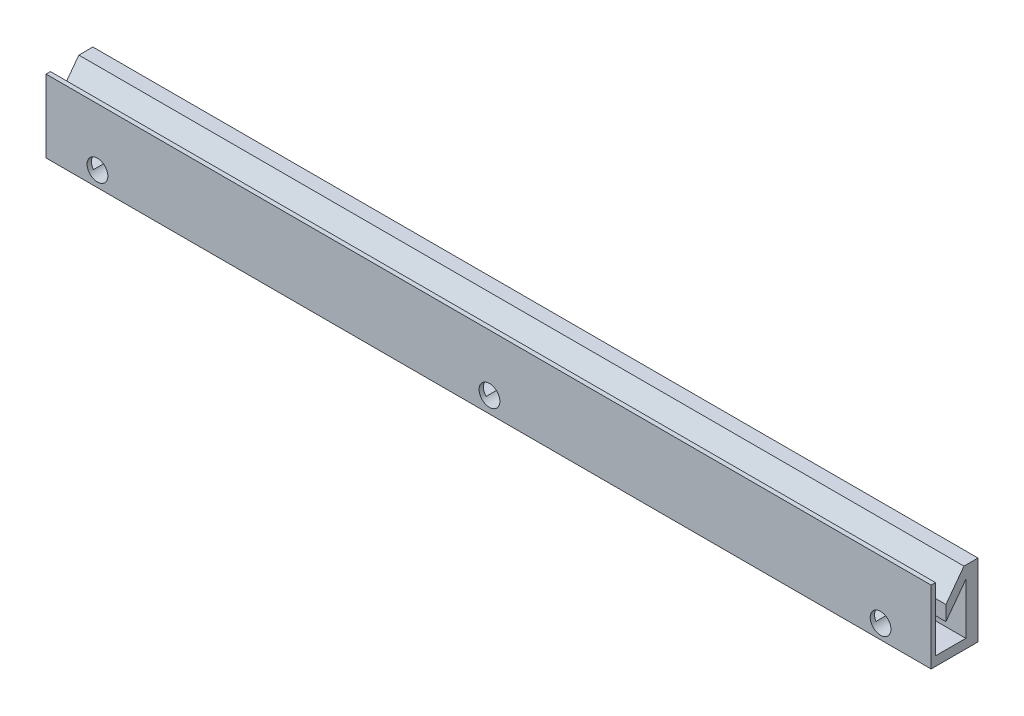
SolidWorks part; units mm, degrees
ref_plane "Front Plane" through (0, 0, 0) normal (0, 0, 1) x (1, 0, 0)
ref_plane "Top Plane" through (0, 0, 0) normal (0, 1, 0) x (1, 0, 0)
ref_plane "Right Plane" through (0, 0, 0) normal (1, 0, 0) x (0, 0, -1)
sketch "Sketch1" plane through (0, 0, 0) normal (1, 0, 0) x (0, 0, -1)
  line L0 (0.083, 0.3694) -> (0.083, 17.0567)
  line L1 (0.083, 17.0567) -> (1.083, 17.0567)
  line L2 (1.083, 17.0567) -> (1.083, 2.4843)
  line L3 (1.083, 2.4843) -> (8.0526, 2.4843)
  line L4 (8.0526, 2.4843) -> (8.0526, 14.2178)
  line L5 (8.0526, 14.2178) -> (3.483, 8.0815)
  line L6 (3.483, 8.0815) -> (3.483, 11.4955)
  line L7 (3.483, 11.4955) -> (7.6243, 17.0567)
  line L8 (7.6243, 17.0567) -> (10.844, 17.0567)
  line L9 (10.844, 17.0567) -> (10.844, 0.3694)
  line L10 (10.844, 0.3694) -> (0.083, 0.3694)
  dimension "D1" = 2.4
  dimension "D2" = 1
extrude "Boss-Extrude1" add sketch "Sketch1" along normal blind 203.2
sketch "Sketch2" plane through (0, 0, -0.083) normal (0, 0, 1) x (1, 0, 0)
  circle A0 centre (11.8144, 3.8654) radius 2.3813
  circle A1 centre (191.5963, 3.6547) radius 2.3813
  circle A2 centre (101.8108, 4.0762) radius 2.3813
extrude "Cut-Extrude1" cut sketch "Sketch2" against normal through all
